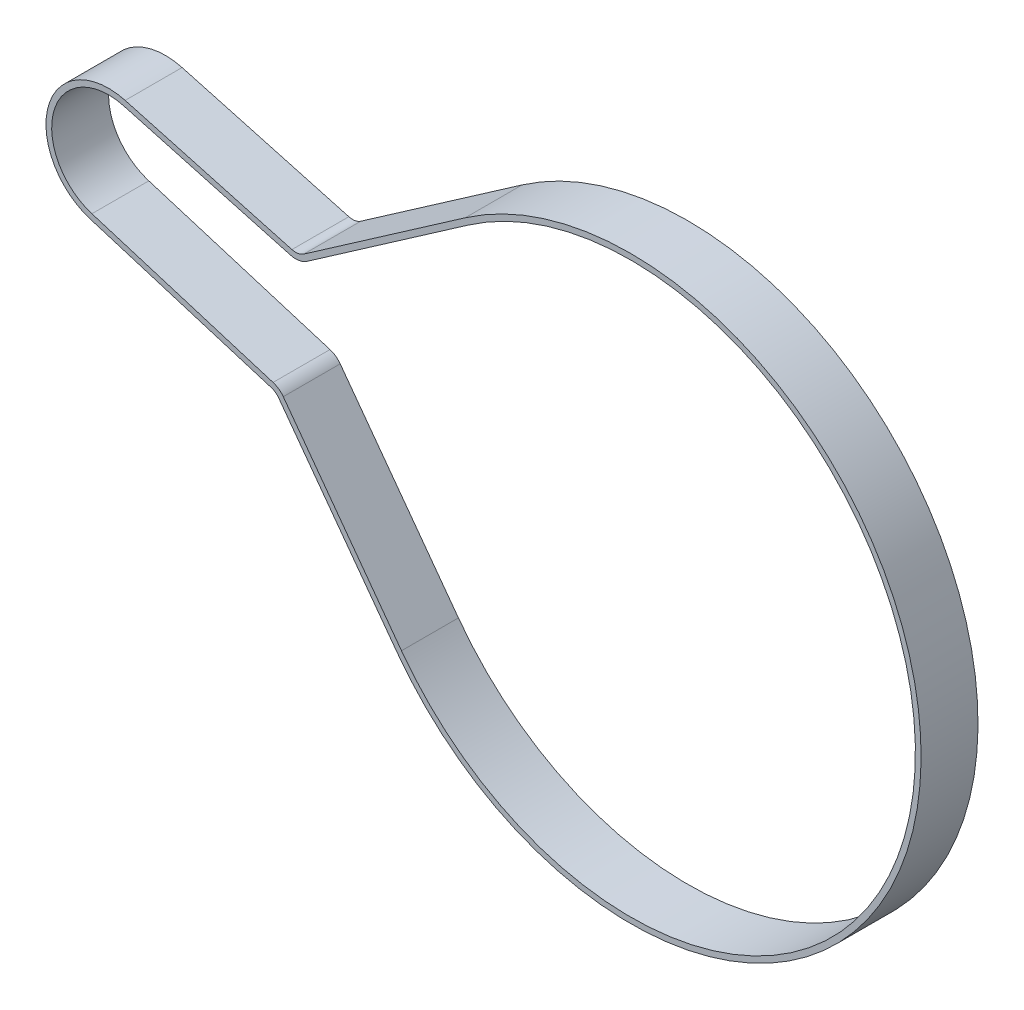
SolidWorks part; units mm, degrees
ref_plane "前视基准面" through (0, 0, 0) normal (0, 0, 1) x (1, 0, 0)
ref_plane "上视基准面" through (0, 0, 0) normal (0, 1, 0) x (1, 0, 0)
ref_plane "右视基准面" through (0, 0, 0) normal (1, 0, 0) x (0, 0, -1)
sketch "Sketch2" plane through (0, 0, 0) normal (0, 0, 1) x (1, 0, 0)
  line L0 (0, 0) -> (1, 0) construction
  line L1 (0, 0) -> (0, 1) construction
  line L2 (-28.5288, 41.0622) -> (-56.8889, 21.3585)
  line L3 (-59.813, 20.8578) -> (-89.1116, 28.9063)
  line L4 (-94.6898, 9.7021) -> (-62.8607, -0.0493)
  line L5 (-61.065, -1.3239) -> (-40.2983, -29.5981)
  arc A0 (-40.2983, -29.5981) -> (-28.5288, 41.0622) centre (0, 0) ccw
  arc A1 (-56.8889, 21.3585) -> (-59.813, 20.8578) centre (-58.8859, 24.2328) cw
  arc A2 (-89.1116, 28.9063) -> (-94.6898, 9.7021) centre (-91.7605, 19.2635) ccw
  arc A3 (-62.8607, -0.0493) -> (-61.065, -1.3239) centre (-63.8859, -3.3957) cw
extrude "Extrude-Thin1" add sketch "Sketch2" against normal blind 10 thin
